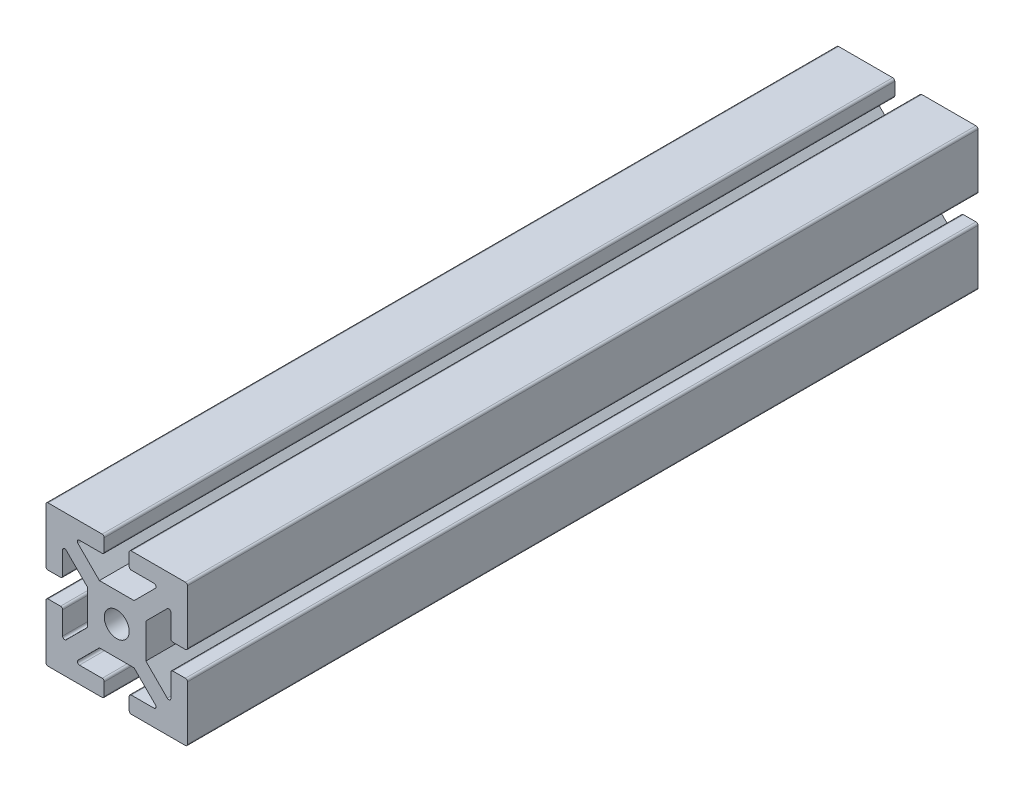
SolidWorks part; units mm, degrees
material "6061-T4 (SS)"
ref_plane "Front Plane" through (0, 0, 0) normal (0, 0, 1) x (1, 0, 0)
ref_plane "Top Plane" through (0, 0, 0) normal (0, 1, 0) x (1, 0, 0)
ref_plane "Right Plane" through (0, 0, 0) normal (1, 0, 0) x (0, 0, -1)
sketch "Sketch1" plane through (0, 0, 0) normal (0, 0, 1) x (1, 0, 0)
  line L0 (2.0858, 3.5) -> (5.0858, 6.5)
  line L1 (-3.5, 3.5) -> (3.5, 3.5)
  line L2 (-3.5, 3.5) -> (-3.5, -3.5)
  line L3 (-3.5, -3.5) -> (3.5, -3.5)
  line L4 (3.5, 3.5) -> (3.5, -3.5)
  line L5 (-3.5, 3.5) -> (3.5, -3.5) construction
  line L6 (-3.5, -3.5) -> (3.5, 3.5) construction
  line L7 (3.5, 2.0858) -> (6.5, 5.0858)
  line L8 (5.0858, 6.5) -> (6.5, 5.0858) construction
  line L9 (-6.5, 6.5) -> (-1.5, 6.5)
  line L10 (-6.5, 6.5) -> (-6.5, 1.5)
  line L11 (-6.5, -6.5) -> (-1.5, -6.5)
  line L12 (6.5, 6.5) -> (6.5, 1.5)
  line L13 (-6.5, 6.5) -> (6.5, -6.5) construction
  line L14 (-6.5, -6.5) -> (6.5, 6.5) construction
  line L15 (0, 6.5) -> (0, -6.5) construction
  line L16 (-5.0858, 6.5) -> (-6.5, 5.0858) construction
  line L17 (-3.5, 2.0858) -> (-6.5, 5.0858)
  line L18 (-2.0858, 3.5) -> (-5.0858, 6.5)
  line L19 (-6.5, 0) -> (6.5, 0) construction
  line L20 (-5.0858, -6.5) -> (-6.5, -5.0858) construction
  line L21 (5.0858, -6.5) -> (6.5, -5.0858) construction
  line L22 (3.5, -2.0858) -> (6.5, -5.0858)
  line L23 (2.0858, -3.5) -> (5.0858, -6.5)
  line L24 (-2.0858, -3.5) -> (-5.0858, -6.5)
  line L25 (-3.5, -2.0858) -> (-6.5, -5.0858)
  line L26 (-1.5, -6.5) -> (-1.5, -8.5)
  line L28 (-8.5, 8.5) -> (-8.5, 1.5)
  line L29 (-8.5, -8.5) -> (-1.5, -8.5)
  line L30 (8.5, 8.5) -> (8.5, 1.5)
  line L31 (-8.5, 8.5) -> (8.5, -8.5) construction
  line L32 (-8.5, -8.5) -> (8.5, 8.5) construction
  line L33 (1.5, -6.5) -> (1.5, -8.5)
  line L34 (-1.5, -7.5) -> (1.5, -7.5) construction
  line L35 (1.5, -8.5) -> (8.5, -8.5)
  line L36 (1.5, -6.5) -> (6.5, -6.5)
  line L37 (-1.5, -6.5) -> (1.5, -6.5) construction
  line L38 (1.5, 6.5) -> (1.5, 8.5)
  line L39 (-1.5, 7.5) -> (1.5, 7.5) construction
  line L40 (-1.5, 6.5) -> (1.5, 6.5) construction
  line L41 (-1.5, 6.5) -> (-1.5, 8.5)
  line L42 (-8.5, 8.5) -> (-1.5, 8.5)
  line L43 (1.5, 6.5) -> (6.5, 6.5)
  line L44 (1.5, 8.5) -> (8.5, 8.5)
  line L45 (6.5, -1.5) -> (8.5, -1.5)
  line L46 (6.5, 1.5) -> (8.5, 1.5)
  line L47 (7.5, 1.5) -> (7.5, -1.5) construction
  line L48 (6.5, 0) -> (7.5, 0) construction
  line L49 (8.5, -1.5) -> (8.5, -8.5)
  line L50 (6.5, -1.5) -> (6.5, -6.5)
  line L51 (6.5, 1.5) -> (6.5, -1.5) construction
  line L52 (-6.5, 0) -> (-7.5, 0) construction
  line L53 (-7.5, 1.5) -> (-7.5, -1.5) construction
  line L54 (-6.5, 1.5) -> (-8.5, 1.5)
  line L55 (-6.5, -1.5) -> (-8.5, -1.5)
  line L56 (-8.5, -1.5) -> (-8.5, -8.5)
  line L57 (-6.5, -1.5) -> (-6.5, -6.5)
  line L58 (-6.5, 1.5) -> (-6.5, -1.5) construction
  circle A0 centre (0, 0) radius 1.5
  point P11 (5.7929, 5.7929)
  point P42 (0, -7.5)
  point P51 (0, 0)
  dimension "D1" = 3
  dimension "D2" = 3.5
  dimension "D3" = 3.5
  dimension "D4" = 3
  dimension "D5" = 3
  dimension "D6" = 2
  dimension "D8" = 2
  dimension "D9" = 3
  dimension "D7" = 2
  dimension "D10" = 3
extrude "Boss-Extrude1" add sketch "Sketch1" along normal blind 95 contours L57 L55 L56 L29 L26 L11 | L45 L50 L36 L33 L35 L49 | L50 L22 L4 L3 L23 L36 | L25 L57 L11 L24 L3 L2 | L4 L1 L2 L3 A0 | L1 L18 L9 L10 L17 L2 | L54 L10 L9 L41 L42 L28 | L12 L46 L30 L44 L38 L43 | L43 L0 L1 L4 L7 L12
fillet "Fillet1" radius 0.25 28 edges at (-6.5, -5.0858, 47.5) (-8.5, -1.5, 47.5) (-6.5, -1.5, 47.5) (-6.5, 5.0858, 47.5) (-6.5, 1.5, 47.5) (-8.5, 1.5, 47.5) (-1.5, 8.5, 47.5) (-5.0858, 6.5, 47.5) (-1.5, 6.5, 47.5) (5.0858, 6.5, 47.5) (1.5, 8.5, 47.5) (1.5, 6.5, 47.5) (6.5, -1.5, 47.5) (8.5, -1.5, 47.5) (8.5, 1.5, 47.5) (6.5, 1.5, 47.5) (6.5, 5.0858, 47.5) (-1.5, -6.5, 47.5) (1.5, -6.5, 47.5) (-1.5, -8.5, 47.5) (1.5, -8.5, 47.5) (-5.0858, -6.5, 47.5) (5.0858, -6.5, 47.5) (6.5, -5.0858, 47.5) (8.5, -8.5, 47.5) (8.5, 8.5, 47.5) (-8.5, 8.5, 47.5) (-8.5, -8.5, 47.5)
equation "\"A\" = 2"
equation "\"B\" = 3"
equation "\"C\"= 95"
equation "\"D1@Sketch1\"=\"B\""
equation "\"D2@Sketch1\"=(\"B\" / 2) + \"A\""
equation "\"D3@Sketch1\"=(\"B\"/2) + \"A\""
equation "\"D4@Sketch1\"=\"B\""
equation "\"D5@Sketch1\"=\"B\""
equation "\"D6@Sketch1\"=\"A\""
equation "\"D8@Sketch1\"=\"A\""
equation "\"D9@Sketch1\"=\"B\""
equation "\"D7@Sketch1\"=\"A\""
equation "\"D10@Sketch1\"=\"B\""
equation "\"D1@Boss-Extrude1\"=\"C\""
